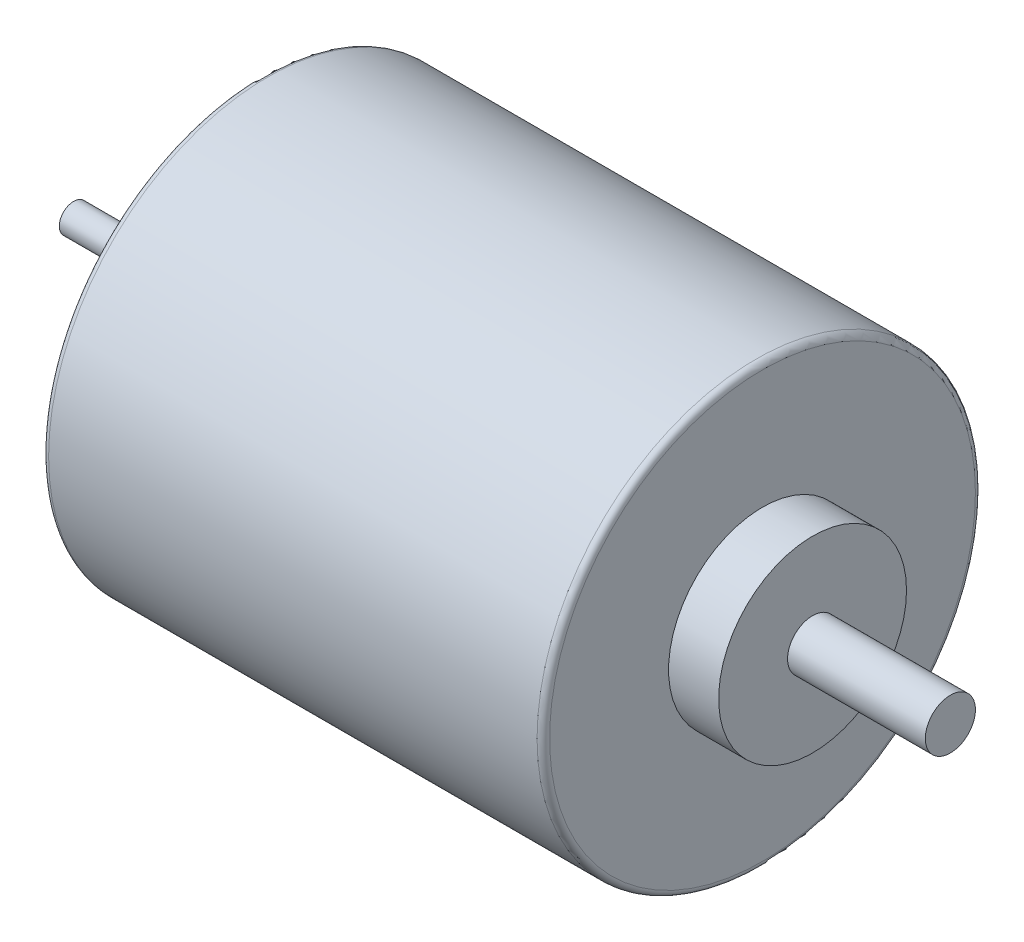
SolidWorks part; units mm, degrees
ref_plane "Alzado" through (0, 0, 0) normal (0, 0, 1) x (1, 0, 0)
ref_plane "Planta" through (0, 0, 0) normal (0, 1, 0) x (1, 0, 0)
ref_plane "Vista lateral" through (0, 0, 0) normal (1, 0, 0) x (0, 0, -1)
sketch "Croquis1" plane through (0, 0, 0) normal (1, 0, 0) x (0, 0, -1)
  circle A0 centre (0, 0) radius 17.5
  dimension "D1" = 35
extrude "Saliente-Extruir1" add sketch "Croquis1" along normal blind 40
sketch "Croquis3" plane through (40, 0, 0) normal (1, 0, 0) x (0, 0, -1)
  circle A0 centre (0, 0) radius 2
  dimension "D1" = 4
extrude "Saliente-Extruir2" add sketch "Croquis3" along normal blind 15 separate body
sketch "Croquis4" plane through (40, 0, 0) normal (1, 0, 0) x (0, 0, -1)
  circle A0 centre (0, 0) radius 7.5
  dimension "D1" = 15
extrude "Saliente-Extruir3" add sketch "Croquis4" along normal blind 4 separate body
sketch "Croquis5" plane through (0, 0, 0) normal (-1, 0, 0) x (0, 0, 1)
  circle A0 centre (0, 0) radius 1.145
  dimension "D1" = 2.29
extrude "Saliente-Extruir4" add sketch "Croquis5" along normal blind 15 separate body
fillet "Redondeo1" radius 0.5 1 edges at (0, 0, -17.5)
fillet "Redondeo2" radius 0.5 1 edges at (40, 0, -17.5)
